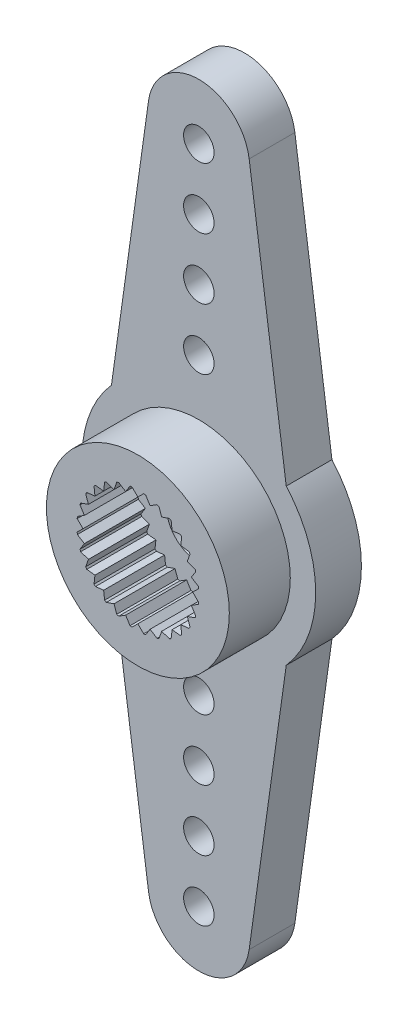
SolidWorks part; units mm, degrees
ref_plane "Plan de face" through (0, 0, 0) normal (0, 0, 1) x (1, 0, 0)
ref_plane "Plan de dessus" through (0, 0, 0) normal (0, 1, 0) x (1, 0, 0)
ref_plane "Plan de droite" through (0, 0, 0) normal (1, 0, 0) x (0, 0, -1)
sketch "Esquisse1" plane through (0, 0, 0) normal (0, 0, 1) x (1, 0, 0)
  circle A0 centre (0, 0) radius 5.75
  circle A1 centre (0, 0) radius 1.6
  dimension "D1" = 11.5
  dimension "D2" = 3.2
extrude "Boss.-Extru.1" add sketch "Esquisse1" along normal blind 5.25
sketch "Esquisse2" plane through (0, 0, 5.25) normal (0, 0, 1) x (1, 0, 0)
  circle A0 centre (0, 0) radius 3
  dimension "D1" = 6
extrude "Enlèv. mat.-Extru.1" cut sketch "Esquisse2" against normal blind 3
sketch "Esquisse3" plane through (0, 0, 5.25) normal (0, 0, 1) x (1, 0, 0)
  circle A0 centre (0, 0) radius 5.75
  circle A1 centre (0, 0) radius 4.5
  circle A2 centre (0, 0) radius 3 construction
  circle A3 centre (0, 0) radius 5.75 construction
  dimension "D1" = 1.5
extrude "Enlèv. mat.-Extru.2" cut sketch "Esquisse3" against normal blind 3
sketch "Esquisse4" plane through (0, 0, 0) normal (0, 0, -1) x (-1, 0, 0)
  line L0 (-4.3, 3.8174) -> (-2.4759, 16.8466)
  line L1 (2.4759, 16.8466) -> (4.3, 3.8174)
  line L2 (-5.2729, 19) -> (6.8365, 19) construction
  line L3 (0, 0) -> (0, 24.2526) construction
  circle A0 centre (0, 0) radius 5.75 construction
  arc A1 (-2.4759, 16.8466) -> (2.4759, 16.8466) centre (0, 16.5) cw
  arc A2 (-4.3, 3.8174) -> (4.3, 3.8174) centre (0, 0) cw
  dimension "D2" = 2.5
  dimension "D1" = 8.6
  dimension "D3" = 19
extrude "Boss.-Extru.2" add sketch "Esquisse4" against normal up to surface (2.25 mm away) up to face at (4.5, 0, 2.25)
pattern_circular "Répétition circulaire1" count 2 every 180 about axis through (0, 0, 0) along (0, 0, 1) of "Boss.-Extru.2"
sketch "Esquisse5" plane through (0, 0, 0) normal (0, 0, -1) x (-1, 0, 0)
  line L0 (0, 0) -> (0, 20.4605) construction
  circle A0 centre (0, 7.25) radius 0.75
  circle A1 centre (0, 10.25) radius 0.75
  circle A2 centre (0, 13.25) radius 0.75
  circle A3 centre (0, 16.25) radius 0.75
  dimension "D5" = 1.5
  dimension "D6" = 1.5
  dimension "D7" = 1.5
  dimension "D8" = 1.5
  dimension "D1" = 7.25
  dimension "D2" = 3
  dimension "D3" = 3
  dimension "D4" = 3
extrude "Enlèv. mat.-Extru.3" cut sketch "Esquisse5" against normal blind 3
pattern_circular "Répétition circulaire2" count 2 every 180 about axis through (0, 0, 0) along (0, 0, 1) of "Enlèv. mat.-Extru.3"
sketch "Esquisse6" plane through (0, 0, 5.25) normal (0, 0, 1) x (1, 0, 0)
  line L0 (-1.598, 3) -> (1.8482, 3) construction
  line L1 (0, 0) -> (0, 5.9454) construction
  line L2 (-0.3, 3) -> (0, 2.7)
  line L3 (0, 2.7) -> (0.3, 3)
  line L4 (0.3, 3) -> (-0.3, 3)
  circle A0 centre (0, 0) radius 3 construction
  dimension "D1" = 0.3
  dimension "D2" = 0.6
extrude "Boss.-Extru.3" add sketch "Esquisse6" against normal up to surface (3 mm away) up to face at (1.6, 0, 2.25)
pattern_circular "Répétition circulaire3" count 28 over 360 about axis through (0, 0, 0) along (0, 0, 1) of "Boss.-Extru.3"
sketch "Esquisse7" plane through (0, 0, 0) normal (0, 0, -1) x (-1, 0, 0)
  circle A0 centre (0, 0) radius 1.6
  circle A1 centre (0, 0) radius 3
  circle A2 centre (0, 0) radius 1.6 construction
  dimension "D1" = 6
extrude "Enlèv. mat.-Extru.4" cut sketch "Esquisse7" against normal blind 1
sketch "Esquisse8" plane through (0, 0, 0) normal (0, 0, -1) x (-1, 0, 0)
  circle A0 centre (0, 0) radius 3.4
  circle A1 centre (0, 0) radius 4.7
  circle A2 centre (0, 0) radius 3 construction
  dimension "D1" = 0.4
  dimension "D2" = 1.3
extrude "Enlèv. mat.-Extru.5" cut sketch "Esquisse8" against normal blind 1
